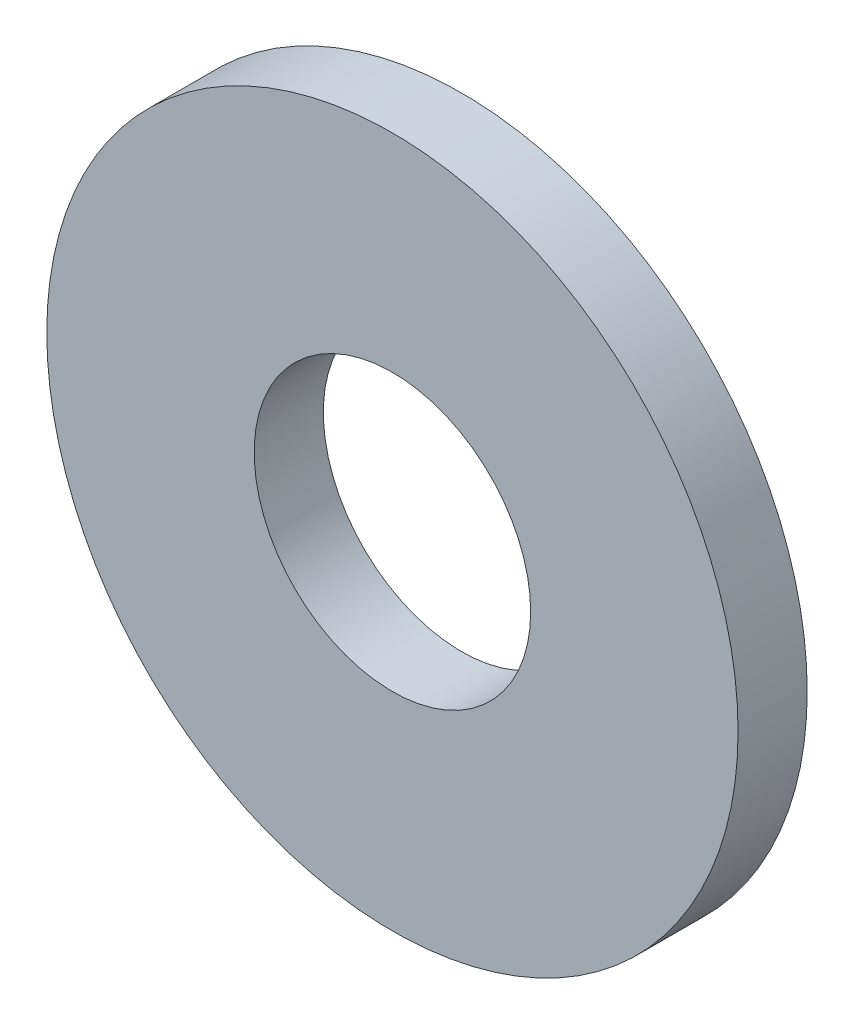
SolidWorks part; units mm, degrees
ref_plane "Plan de face" through (0, 0, 0) normal (0, 0, 1) x (1, 0, 0)
ref_plane "Plan de dessus" through (0, 0, 0) normal (0, 1, 0) x (1, 0, 0)
ref_plane "Plan de droite" through (0, 0, 0) normal (1, 0, 0) x (0, 0, -1)
sketch "Esquisse1" plane through (0, 0, 0) normal (0, 0, 1) x (1, 0, 0)
  circle A0 centre (0, 0) radius 2
  circle A1 centre (0, 0) radius 5
  dimension "D1" = 10
  dimension "D2" = 4
extrude "Boss.-Extru.1" add sketch "Esquisse1" along normal blind 1
